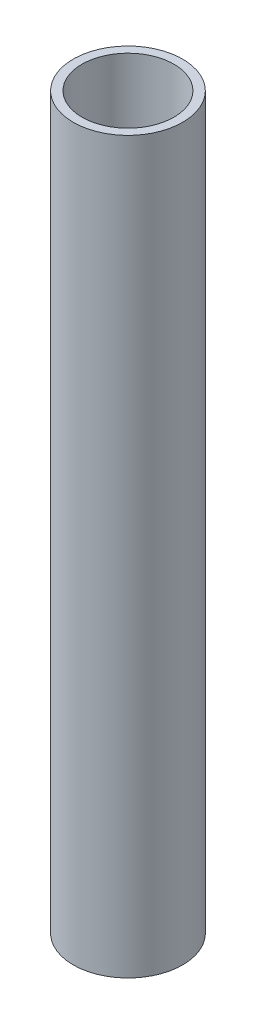
SolidWorks part; units mm, degrees
ref_plane "Front Plane" through (0, 0, 0) normal (0, 0, 1) x (1, 0, 0)
ref_plane "Top Plane" through (0, 0, 0) normal (0, 1, 0) x (1, 0, 0)
ref_plane "Right Plane" through (0, 0, 0) normal (1, 0, 0) x (0, 0, -1)
sketch "Sketch1" plane through (0, 0, 0) normal (0, 1, 0) x (1, 0, 0)
  circle A0 centre (0, 0) radius 9.525
  dimension "D1" = 19.05
extrude "Boss-Extrude1" add sketch "Sketch1" along normal blind 127
sketch "Sketch2" plane through (0, 127, 0) normal (0, 1, 0) x (1, 0, 0)
  circle A0 centre (0, 0) radius 8.001
  dimension "D1" = 16.002
extrude "Cut-Extrude1" cut sketch "Sketch2" against normal through all
